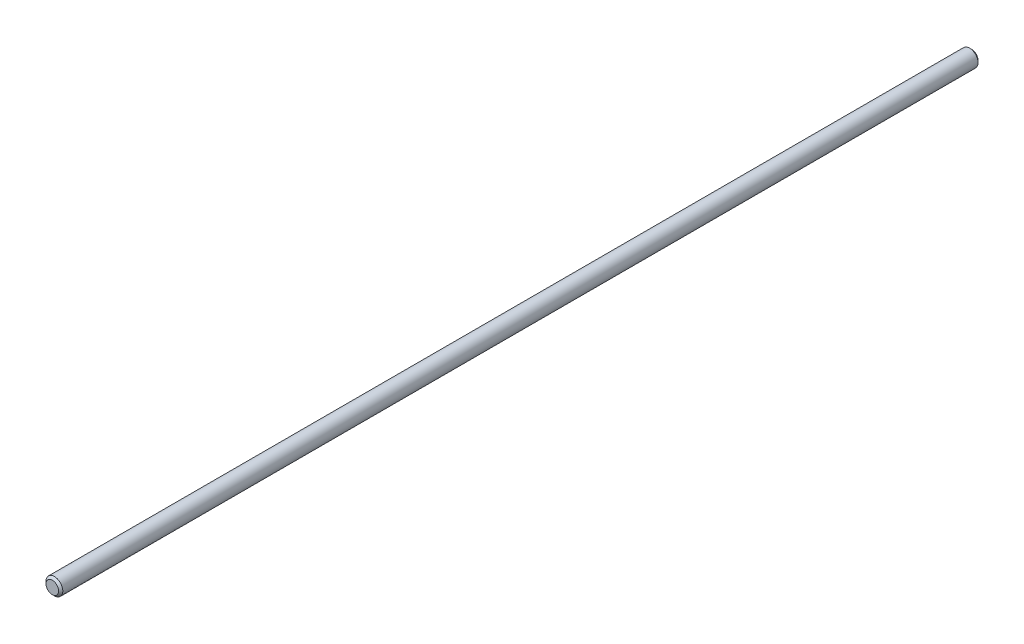
SolidWorks part; units mm, degrees
ref_plane "Piano frontale" through (0, 0, 0) normal (0, 0, 1) x (1, 0, 0)
ref_plane "Piano superiore" through (0, 0, 0) normal (0, 1, 0) x (1, 0, 0)
ref_plane "Piano destro" through (0, 0, 0) normal (1, 0, 0) x (0, 0, -1)
sketch "Schizzo1" plane through (0, 0, 0) normal (0, 0, 1) x (1, 0, 0)
  circle A0 centre (0, 0) radius 4
  dimension "D1" = 8
extrude "Estrusione-Estrusione1" add sketch "Schizzo1" along normal blind 438
chamfer "Smusso1" distance 1 angle 45 2 edges at (4, 0, 0) (4, 0, 438)
sketch "Schizzo2" plane through (0, 0, 0) normal (0, 1, 0) x (1, 0, 0)
  line L0 (4, -1) -> (4, -437) construction
